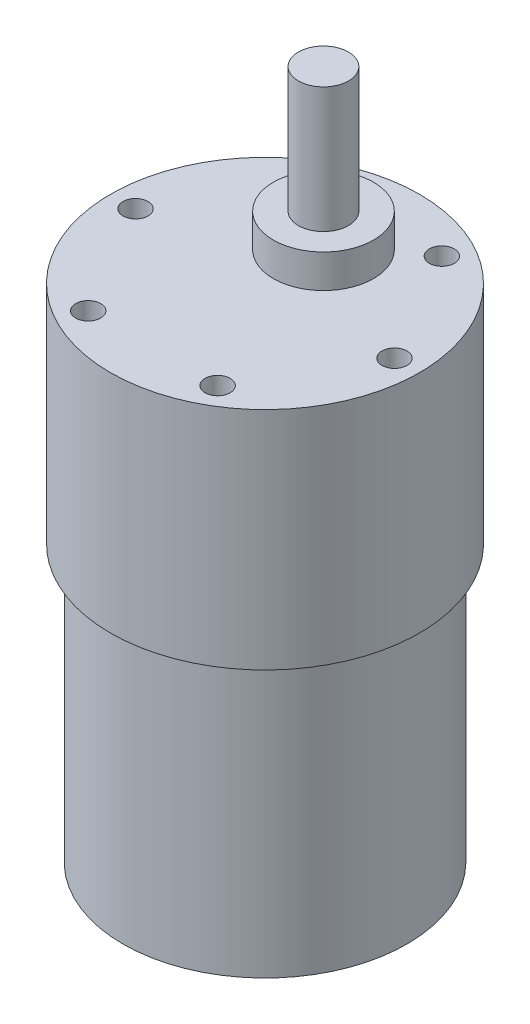
SolidWorks part; units mm, degrees
ref_plane "前视基准面" through (0, 0, 0) normal (0, 0, 1) x (1, 0, 0)
ref_plane "上视基准面" through (0, 0, 0) normal (0, 1, 0) x (1, 0, 0)
ref_plane "右视基准面" through (0, 0, 0) normal (1, 0, 0) x (0, 0, -1)
sketch "草图1" plane through (0, 0, 0) normal (0, 1, 0) x (1, 0, 0)
  circle A0 centre (0, 0) radius 17
  dimension "D1" = 34
extrude "凸台-拉伸1" add sketch "草图1" along normal blind 33
sketch "草图2" plane through (0, 33, 0) normal (0, 1, 0) x (1, 0, 0)
  circle A0 centre (0, 0) radius 18.5
  dimension "D1" = 37
extrude "凸台-拉伸2" add sketch "草图2" along normal blind 27
sketch "草图3" plane through (0, 60, 0) normal (0, 1, 0) x (1, 0, 0)
  circle A0 centre (0, 7) radius 6
  dimension "D1" = 12
  dimension "D2" = 7
extrude "凸台-拉伸3" add sketch "草图3" along normal blind 4
sketch "草图4" plane through (0, 64, 0) normal (0, 1, 0) x (1, 0, 0)
  circle A0 centre (0, 7) radius 3
  dimension "D1" = 6
extrude "凸台-拉伸5" add sketch "草图4" along normal blind 15
sketch "草图6" plane through (0, 60, 0) normal (0, 1, 0) x (1, 0, 0)
  line L0 (0, 0) -> (15.5, 0) construction
  circle A0 centre (0, 0) radius 15.5 construction
  circle A1 centre (7.75, 13.4234) radius 1.5
  circle A2 centre (15.5, 0) radius 1.5
  circle A3 centre (7.75, -13.4234) radius 1.5
  circle A4 centre (-7.75, -13.4234) radius 1.5
  circle A5 centre (-15.5, 0) radius 1.5
  circle A6 centre (-7.75, 13.4234) radius 1.5
  point P17 (0, 0)
  point P19 (0, 0)
  dimension "D1" = 31
  dimension "D2" = 3
  dimension "D3" = 60
  dimension "D4" = 6
extrude "切除-拉伸1" cut sketch "草图6" against normal blind 5
